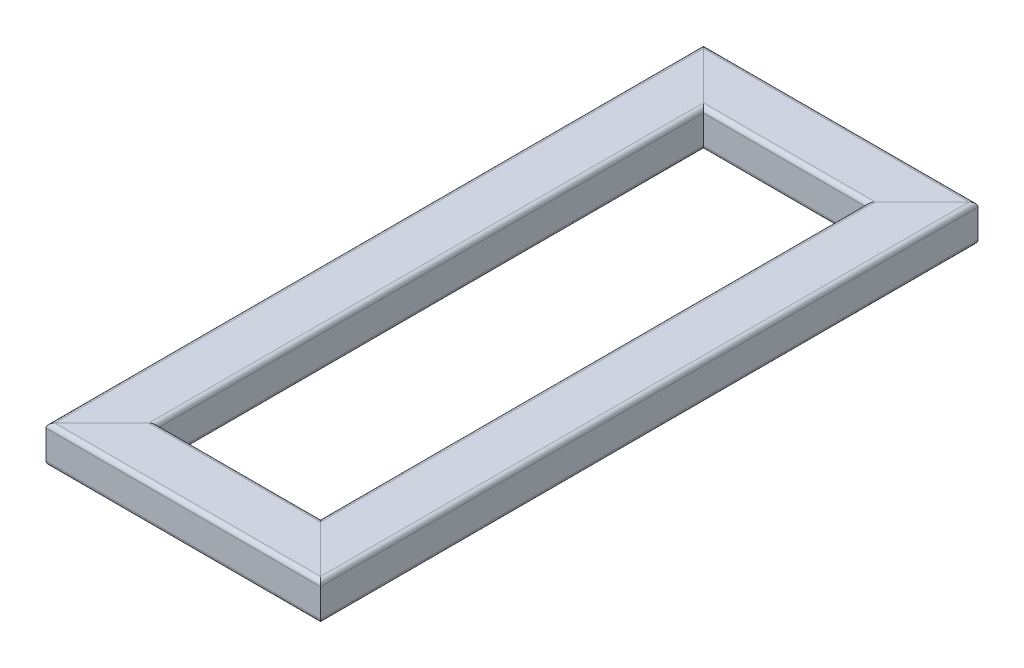
SolidWorks part; units mm, degrees
material "ASTM A36 Acero"
ref_plane "Alzado" through (0, 0, 0) normal (0, 0, 1) x (1, 0, 0)
ref_plane "Planta" through (0, 0, 0) normal (0, 1, 0) x (1, 0, 0)
ref_plane "Vista lateral" through (0, 0, 0) normal (1, 0, 0) x (0, 0, -1)
sketch "Croquis1" plane through (0, 0, 0) normal (0, 1, 0) x (1, 0, 0)
  line L1 (-187.5, 449) -> (187.5, 449)
  line L2 (-187.5, 449) -> (-187.5, -449)
  line L3 (-187.5, -449) -> (187.5, -449)
  line L4 (187.5, 449) -> (187.5, -449)
  line L5 (-187.5, 449) -> (187.5, -449) construction
  line L6 (-187.5, -449) -> (187.5, 449) construction
  point P0 (0, 0)
  dimension "D1" = 898
  dimension "D2" = 375
other "Tubo rectangular 3 X 2 X 0.25(1)"
ref_plane "Plano1" through (-149.4, 25.4, -449) normal (0, 0, 1) x (1, 0, 0)
sketch "Sketch1" plane through (-149.4, 25.4, -449) normal (0, 0, 1) x (1, 0, 0)
  line L0 (-32.1, -23.4) -> (32.1, -23.4)
  line L1 (-36.1, -19.4) -> (-36.1, 19.4)
  line L2 (32.1, 23.4) -> (-32.1, 23.4)
  line L3 (36.1, 19.4) -> (36.1, -19.4)
  line L4 (-32.1, -25.4) -> (32.1, -25.4)
  line L5 (-38.1, -19.4) -> (-38.1, 19.4)
  line L6 (32.1, 25.4) -> (-32.1, 25.4)
  line L7 (38.1, 19.4) -> (38.1, -19.4)
  line L8 (0, 0) -> (38.1, 0) construction
  line L9 (0, 0) -> (0, 25.4) construction
  arc A0 (38.1, 19.4) -> (32.1, 25.4) centre (32.1, 19.4) ccw
  arc A1 (32.1, -25.4) -> (38.1, -19.4) centre (32.1, -19.4) ccw
  arc A2 (-38.1, -19.4) -> (-32.1, -25.4) centre (-32.1, -19.4) ccw
  arc A3 (-32.1, 25.4) -> (-38.1, 19.4) centre (-32.1, 19.4) ccw
  arc A4 (-32.1, 23.4) -> (-36.1, 19.4) centre (-32.1, 19.4) ccw
  arc A5 (36.1, 19.4) -> (32.1, 23.4) centre (32.1, 19.4) ccw
  arc A6 (32.1, -23.4) -> (36.1, -19.4) centre (32.1, -19.4) ccw
  arc A7 (-36.1, -19.4) -> (-32.1, -23.4) centre (-32.1, -19.4) ccw
  point P3 (0, -25.4)
  point P4 (-38.1, 0)
  point P5 (0, 0)
  point P6 (38.1, -25.4)
  point P7 (-38.1, -25.4)
  point P8 (-38.1, 25.4)
  point P33 (0, 0)
  point P35 (38.1, 25.4)
  point P36 (38.1, 0)
  point P37 (0, 25.4)
  dimension "D1" = 6
  dimension "Thickness" = 2
  dimension "V_leg" = 50.8
  dimension "H_leg" = 76.2
